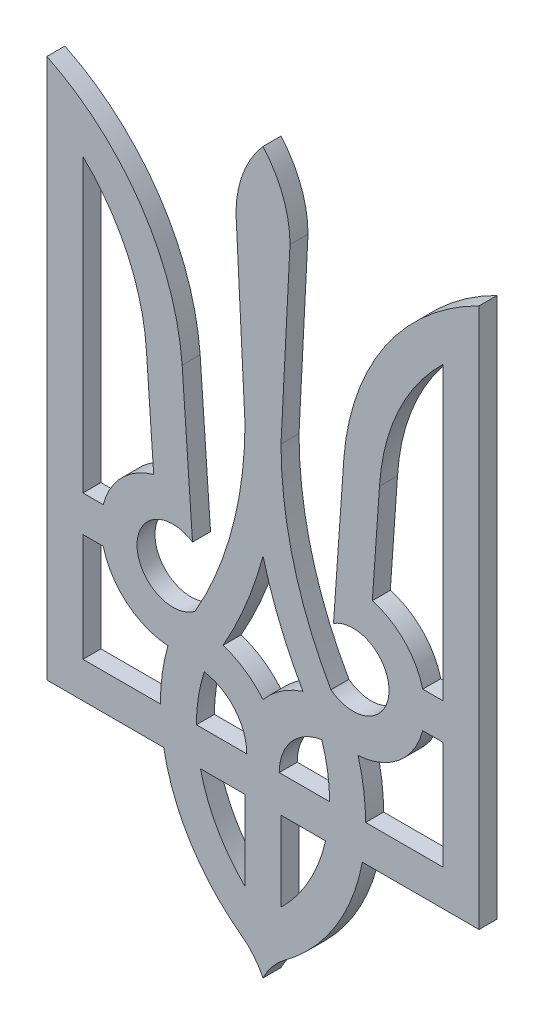
SolidWorks part; units mm, degrees
ref_plane "Спереди" through (0, 0, 0) normal (0, 0, 1) x (1, 0, 0)
ref_plane "Сверху" through (0, 0, 0) normal (0, 1, 0) x (1, 0, 0)
ref_plane "Справа" through (0, 0, 0) normal (1, 0, 0) x (0, 0, -1)
sketch "Эскиз1" plane through (0, 0, 0) normal (0, 0, 1) x (1, 0, 0)
  line B0 (18.5, -49.8157) -> (4.5, -49.8157)
  line B1 (5, -59.8157) -> (17.3748, -59.8157)
  line B2 (5, -81.9521) -> (5, -59.8157)
  line B3 (28.5, -49.8157) -> (50, -49.8157)
  line B4 (50, -49.8157) -> (50, -19.8157)
  line B5 (44.3649, -19.8157) -> (50, -19.8157)
  line B6 (44.3649, -9.8157) -> (50, -9.8157)
  line B7 (50, -9.8157) -> (50, 71.0935)
  line B8 (32.3556, 32.9857) -> (30.3604, 4.4526)
  line B9 (5, 29.4343) -> (7.5, 78.6843)
  line B10 (22.4495, 34.6773) -> (19.5761, -6.4145)
  line B11 (60, -59.8157) -> (60, 90.1843)
  line B12 (27.5833, -59.8157) -> (60, -59.8157)
  line B13 (-44.3649, -19.8157) -> (-50, -19.8157)
  line B14 (-5, -81.9521) -> (-5, -59.8157)
  line B15 (-50, -9.8157) -> (-50, 71.0935)
  line B16 (-44.3649, -9.8157) -> (-50, -9.8157)
  line B17 (-32.3556, 32.9857) -> (-30.3604, 4.4526)
  line B18 (-50, -49.8157) -> (-50, -19.8157)
  line B19 (-28.5, -49.8157) -> (-50, -49.8157)
  line B20 (-5, -59.8157) -> (-17.3748, -59.8157)
  line B21 (-18.5, -49.8157) -> (-4.5, -49.8157)
  line B22 (-27.5833, -59.8157) -> (-60, -59.8157)
  line B23 (-60, -59.8157) -> (-60, 90.1843)
  line B24 (-22.4495, 34.6773) -> (-19.5761, -6.4145)
  line B25 (-5, 29.4343) -> (-7.5, 78.6843)
  arc B26 (18.5, -49.8157) -> (16.3222, -35.9861) centre (-26.5, -49.8157) ccw
  arc B27 (16.3222, -35.9861) -> (4.5, -49.8157) centre (18.5, -49.8157) ccw
  arc B28 (5, -81.9521) -> (17.3748, -59.8157) centre (-26.5, -49.8157) ccw
  arc B29 (28.5, -49.8157) -> (26.4011, -34.7666) centre (-26.5, -49.8157) ccw
  arc B30 (26.4011, -34.7666) -> (44.3649, -19.8157) centre (25, -14.8157) ccw
  arc B31 (44.3649, -9.8157) -> (30.3604, 4.4526) centre (25, -14.8157) ccw
  arc B32 (50, 71.0935) -> (32.3556, 32.9857) centre (90, 29.4343) ccw
  arc B33 (11.0914, -26.9878) -> (0, -34.5268) centre (18.5, -49.8157) ccw
  arc B34 (0, 0) -> (11.0914, -26.9878) centre (110, 29.4343) ccw
  arc B35 (7.5, 78.6843) -> (0, 98.5274) centre (-22.5, 78.6843) ccw
  arc B36 (5, 29.4343) -> (18.8639, -22.7118) centre (110, 29.4343) ccw
  arc B37 (18.8639, -22.7118) -> (19.5761, -6.4145) centre (25, -14.8157) ccw
  arc B38 (60, 90.1843) -> (22.4495, 34.6773) centre (90, 29.4343) ccw
  arc B39 (5.9458, -94.226) -> (27.5833, -59.8157) centre (-26.5, -49.8157) ccw
  arc B40 (5.9458, -94.226) -> (0, -101.4726) centre (18.004, -110.1822) ccw
  arc B41 (-32.3556, 32.9857) -> (-50, 71.0935) centre (-90, 29.4343) ccw
  arc B42 (-16.3222, -35.9861) -> (-18.5, -49.8157) centre (26.5, -49.8157) ccw
  arc B43 (-30.3604, 4.4526) -> (-44.3649, -9.8157) centre (-25, -14.8157) ccw
  arc B44 (-26.4011, -34.7666) -> (-28.5, -49.8157) centre (26.5, -49.8157) ccw
  arc B45 (-44.3649, -19.8157) -> (-26.4011, -34.7666) centre (-25, -14.8157) ccw
  arc B46 (-17.3748, -59.8157) -> (-5, -81.9521) centre (26.5, -49.8157) ccw
  arc B47 (-4.5, -49.8157) -> (-16.3222, -35.9861) centre (-18.5, -49.8157) ccw
  arc B48 (0, -101.4726) -> (-5.9458, -94.226) centre (-18.004, -110.1822) ccw
  arc B49 (-27.5833, -59.8157) -> (-5.9458, -94.226) centre (26.5, -49.8157) ccw
  arc B50 (-22.4495, 34.6773) -> (-60, 90.1843) centre (-90, 29.4343) ccw
  arc B51 (-19.5761, -6.4145) -> (-18.8639, -22.7118) centre (-25, -14.8157) ccw
  arc B52 (-18.8639, -22.7118) -> (-5, 29.4343) centre (-110, 29.4343) ccw
  arc B53 (0, 98.5274) -> (-7.5, 78.6843) centre (22.5, 78.6843) ccw
  arc B54 (-11.0914, -26.9878) -> (0, 0) centre (-110, 29.4343) ccw
  arc B55 (0, -34.5268) -> (-11.0914, -26.9878) centre (-18.5, -49.8157) ccw
sketch_block_instance "Блок1-1"
sketch_block "Блок1"
extrude "Бобышка-Вытянуть1" add sketch "Эскиз1" along normal blind 5
scale "Масштаб1" scale about centroid uniform scaling yes scale factor 0.6
